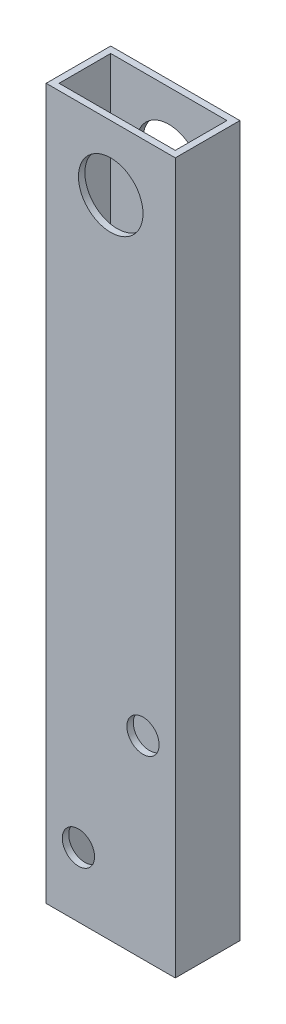
SolidWorks part; units mm, degrees
ref_plane "Front Plane" through (0, 0, 0) normal (0, 0, 1) x (1, 0, 0)
ref_plane "Top Plane" through (0, 0, 0) normal (0, 1, 0) x (1, 0, 0)
ref_plane "Right Plane" through (0, 0, 0) normal (1, 0, 0) x (0, 0, -1)
sketch "Sketch1" plane through (0, 0, 0) normal (0, 1, 0) x (1, 0, 0)
  line L0 (2.54, 22.86) -> (48.26, 22.86)
  line L1 (0, 0) -> (50.8, 0)
  line L2 (0, 0) -> (0, 25.4)
  line L3 (0, 25.4) -> (50.8, 25.4)
  line L4 (50.8, 0) -> (50.8, 25.4)
  line L5 (48.26, 2.54) -> (48.26, 22.86)
  line L6 (2.54, 2.54) -> (48.26, 2.54)
  line L7 (2.54, 2.54) -> (2.54, 22.86)
  dimension "D1" = 25.4
  dimension "D2" = 50.8
  dimension "D3" = 2.54
extrude "Boss-Extrude1" add sketch "Sketch1" along normal blind 279.4
sketch "Sketch2" plane through (0, 0, 0) normal (0, 0, 1) x (1, 0, 0)
  line L0 (50.8, 279.4) -> (50.8, 0) construction
  line L1 (0, 279.4) -> (50.8, 279.4) construction
  line L2 (0, 0) -> (50.8, 0) construction
  circle A0 centre (12.7, 25.4) radius 6.35
  circle A1 centre (25.4, 254) radius 12.7
  dimension "D1" = 25.4
  dimension "D2" = 25.4
  dimension "D3" = 25.4
  dimension "D4" = 12.7
  dimension "D5" = 38.1
  dimension "D6" = 25.4
extrude "Cut-Extrude1" cut sketch "Sketch2" against normal through all
sketch "Sketch3" plane through (0, 0, -25.4) normal (0, 0, -1) x (-1, 0, 0)
  line L0 (0, 279.4) -> (0, 0) construction
  line L1 (-50.8, 0) -> (0, 0) construction
  circle A0 centre (-38.1, 76.2) radius 6.35
  dimension "D1" = 12.7
  dimension "D2" = 38.1
  dimension "D3" = 76.2
extrude "Cut-Extrude2" cut sketch "Sketch3" against normal through all
